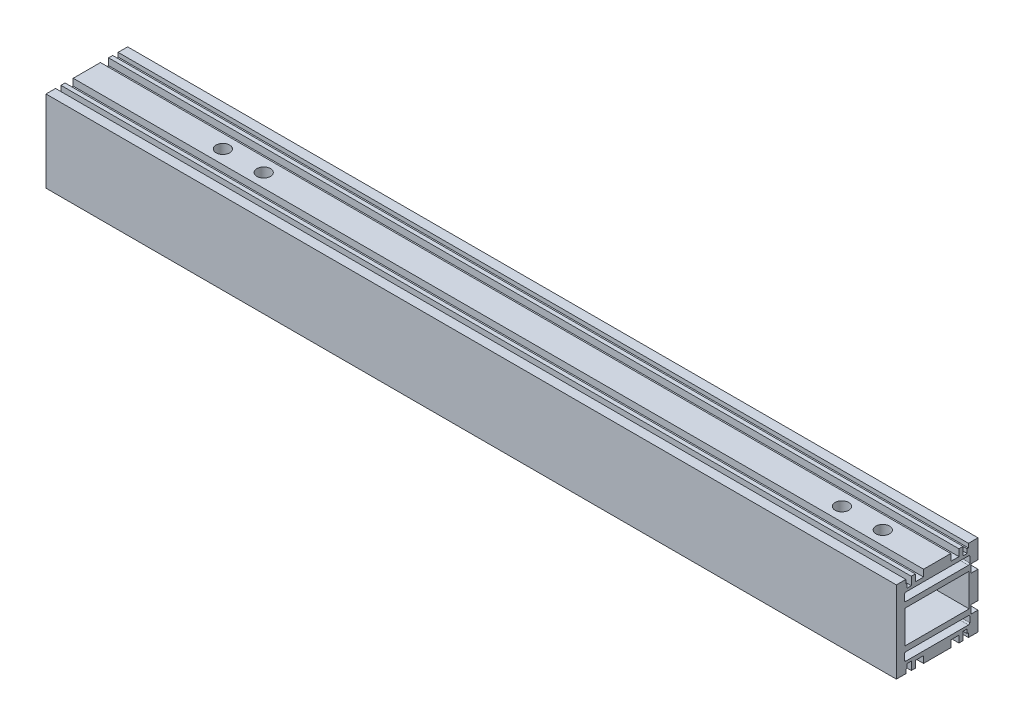
SolidWorks part; units mm, degrees
ref_plane "前视基准面" through (0, 0, 0) normal (0, 0, 1) x (1, 0, 0)
ref_plane "上视基准面" through (0, 0, 0) normal (0, 1, 0) x (1, 0, 0)
ref_plane "右视基准面" through (0, 0, 0) normal (1, 0, 0) x (0, 0, -1)
sketch "草图1" plane through (0, 0, 0) normal (1, 0, 0) x (0, 0, -1)
  line L0 (-15, 15) -> (15, -15) construction
  line L1 (-15, 15) -> (-11.5, 15)
  line L2 (-15, 15) -> (-15, -15)
  line L3 (-15, -15) -> (-11.5, -15)
  line L4 (15, 15) -> (15, 8)
  line L5 (15, 15) -> (-15, -15) construction
  line L6 (-11.5, 15) -> (-11.5, 13.5)
  line L7 (-11.5, 13.5) -> (-11, 13.5)
  line L8 (-11, 13.5) -> (-11, 12)
  line L9 (-11, 12) -> (-9.5, 12)
  line L10 (-9.5, 12) -> (-9.5, 15)
  line L11 (-9.5, 15) -> (-8, 15)
  line L12 (-8, 15) -> (-8, 12.5)
  line L13 (-8, 12.5) -> (-5, 12.5)
  line L14 (-5, 12.5) -> (-5, 15)
  line L15 (-5, 15) -> (5, 15)
  line L16 (0, 21.5201) -> (0, -18.309) construction
  line L17 (0, 55) -> (0, -55) construction
  line L18 (5, 12.5) -> (5, 15)
  line L19 (8, 12.5) -> (5, 12.5)
  line L20 (8, 15) -> (8, 12.5)
  line L21 (9.5, 15) -> (8, 15)
  line L22 (9.5, 12) -> (9.5, 15)
  line L23 (11, 12) -> (9.5, 12)
  line L24 (11, 13.5) -> (11, 12)
  line L25 (11.5, 13.5) -> (11, 13.5)
  line L26 (11.5, 15) -> (11.5, 13.5)
  line L27 (8, 15) -> (9.5, 15)
  line L28 (11.5, 15) -> (15, 15)
  line L29 (-19.8303, 0) -> (22.13, 0) construction
  line L30 (55, 0) -> (-55, 0) construction
  line L31 (8, -15) -> (9.5, -15)
  line L32 (11.5, -15) -> (11.5, -13.5)
  line L33 (11.5, -13.5) -> (11, -13.5)
  line L34 (11, -13.5) -> (11, -12)
  line L35 (11, -12) -> (9.5, -12)
  line L36 (9.5, -12) -> (9.5, -15)
  line L37 (9.5, -15) -> (8, -15)
  line L38 (8, -15) -> (8, -12.5)
  line L39 (8, -12.5) -> (5, -12.5)
  line L40 (5, -12.5) -> (5, -15)
  line L41 (-5, -15) -> (5, -15)
  line L42 (-5, -12.5) -> (-5, -15)
  line L43 (-8, -12.5) -> (-5, -12.5)
  line L44 (-8, -15) -> (-8, -12.5)
  line L45 (-9.5, -15) -> (-8, -15)
  line L46 (-9.5, -12) -> (-9.5, -15)
  line L47 (-11, -12) -> (-9.5, -12)
  line L48 (-11, -13.5) -> (-11, -12)
  line L49 (-11.5, -13.5) -> (-11, -13.5)
  line L50 (-11.5, -15) -> (-11.5, -13.5)
  line L51 (-9.5, -15) -> (-8, -15)
  line L52 (-5, -15) -> (5, -15)
  line L53 (8, -15) -> (9.5, -15)
  line L54 (11.5, -15) -> (15, -15)
  line L55 (15, 8) -> (12.5, 8)
  line L56 (12.5, 8) -> (12.5, 5)
  line L57 (12.5, 5) -> (15, 5)
  line L58 (12.5, -5) -> (15, -5)
  line L59 (12.5, -8) -> (12.5, -5)
  line L60 (15, -8) -> (12.5, -8)
  line L61 (15, 5) -> (15, -5)
  line L62 (15, -8) -> (15, -15)
  line L63 (12, -10.5) -> (12, -8.5)
  line L64 (-11.5, 11) -> (11.5, 11)
  line L65 (-12, 10.5) -> (-12, 8.5)
  line L66 (-11.5, 8) -> (11.5, 8)
  line L67 (12, 10.5) -> (12, 8.5)
  line L68 (-11.5, -8) -> (11.5, -8)
  line L69 (-12, -10.5) -> (-12, -8.5)
  line L70 (-11.5, -11) -> (11.5, -11)
  line L72 (-11.75, 6) -> (11.75, 6)
  line L73 (-11.75, 6) -> (-11.75, -6)
  line L74 (-11.75, -6) -> (11.75, -6)
  line L75 (11.75, 6) -> (11.75, -6)
  arc A0 (12, 8.5) -> (11.5, 8) centre (11.5, 8.5) cw
  arc A1 (11.5, 11) -> (12, 10.5) centre (11.5, 10.5) cw
  arc A2 (-11.5, 11) -> (-12, 10.5) centre (-11.5, 10.5) ccw
  arc A3 (-11.5, 8) -> (-12, 8.5) centre (-11.5, 8.5) cw
  arc A8 (-11.5, -8) -> (-12, -8.5) centre (-11.5, -8.5) ccw
  arc A9 (-11.5, -11) -> (-12, -10.5) centre (-11.5, -10.5) cw
  arc A10 (11.5, -11) -> (12, -10.5) centre (11.5, -10.5) ccw
  arc A11 (12, -8.5) -> (11.5, -8) centre (11.5, -8.5) ccw
  point P69 (12, 11)
  point P72 (-12, 11)
  point P77 (-11, -13.5)
  point P80 (11, -13.5)
  point P83 (11, 13.5)
  point P86 (-11, 13.5)
  point P99 (-12, -11)
  point P100 (12, -11)
  dimension "D17" = 0.5
  dimension "D1" = 3.5
  dimension "D2" = 1.5
  dimension "D3" = 0.5
  dimension "D4" = 1.5
  dimension "D5" = 3
  dimension "D6" = 30
  dimension "D7" = 30
  dimension "D8" = 1.5
  dimension "D9" = 2.5
  dimension "D10" = 3
  dimension "D11" = 2.5
  dimension "D12" = 7
  dimension "D13" = 3
  dimension "D14" = 4
  dimension "D15" = 3
  dimension "D16" = 24
  dimension "D19" = 23.5
  dimension "D20" = 12
extrude "凸台-拉伸1" add sketch "草图1" along normal mid plane 312.5
hole_wizard "M6 螺纹孔1" positions "草图3" profile "草图2" tap size "M6" standard "GB"
sketch "草图3" plane through (0, 15, 0) normal (0, 1, 0) x (1, 0, 0)
  point P0 (136.25, 0)
  point P3 (121.25, 0)
  point P6 (-91.25, 0)
  point P9 (-106.25, 0)
sketch "草图2" plane through (136.25, 15, 0) normal (1, 0, 0) x (0, 0, 1)
  line L0 (0, 0) -> (0, 20.5022)
  line L1 (0, 20.5022) -> (2.5, 19)
  line L2 (2.5, 19) -> (2.5, 0)
  line L5 (2.5, 0) -> (0, 0)
  line L10 (0, 20.5022) -> (-2.5, 19) construction
  line L11 (0, -6.35) -> (0, 107.95) construction
  dimension "螺纹孔钻头直径" = 5
  dimension "螺纹孔钻头深度" = 19
  dimension "导头角度" = 118
cosmetic thread "孔螺蚊线1" parameters "D1"=9, "D2"=6
cosmetic thread "孔螺蚊线2" parameters "D1"=9, "D2"=6
cosmetic thread "孔螺蚊线3" parameters "D1"=9, "D2"=6
cosmetic thread "孔螺蚊线4" parameters "D1"=9, "D2"=6
